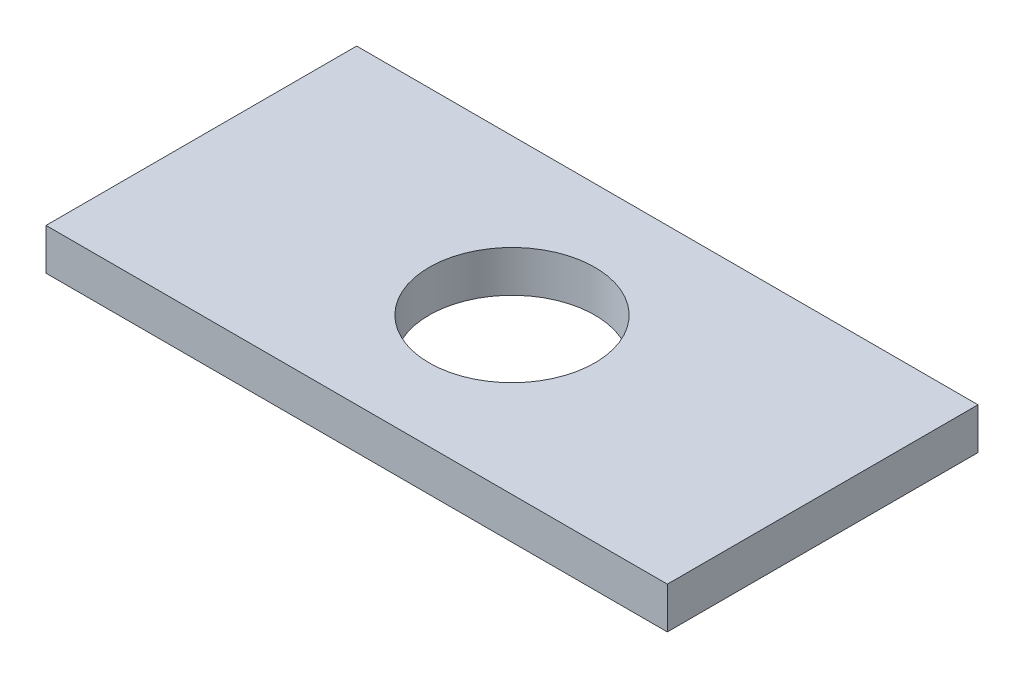
SolidWorks part; units mm, degrees
ref_plane "Front Plane" through (0, 0, 0) normal (0, 0, 1) x (1, 0, 0)
ref_plane "Top Plane" through (0, 0, 0) normal (0, 1, 0) x (1, 0, 0)
ref_plane "Right Plane" through (0, 0, 0) normal (1, 0, 0) x (0, 0, -1)
sketch "Sketch1" plane through (0, 0, 0) normal (0, 1, 0) x (1, 0, 0)
  line L1 (0, 0) -> (30, 0)
  line L2 (0, 0) -> (0, 15)
  line L3 (0, 15) -> (30, 15)
  line L4 (30, 0) -> (30, 15)
  circle A0 centre (15, 7.5) radius 4
  dimension "D3" = 8
  dimension "D1" = 30
  dimension "D2" = 15
extrude "Boss-Extrude2" add sketch "Sketch1" along normal blind 2 contours A0 | L3 L4 L1 L2
